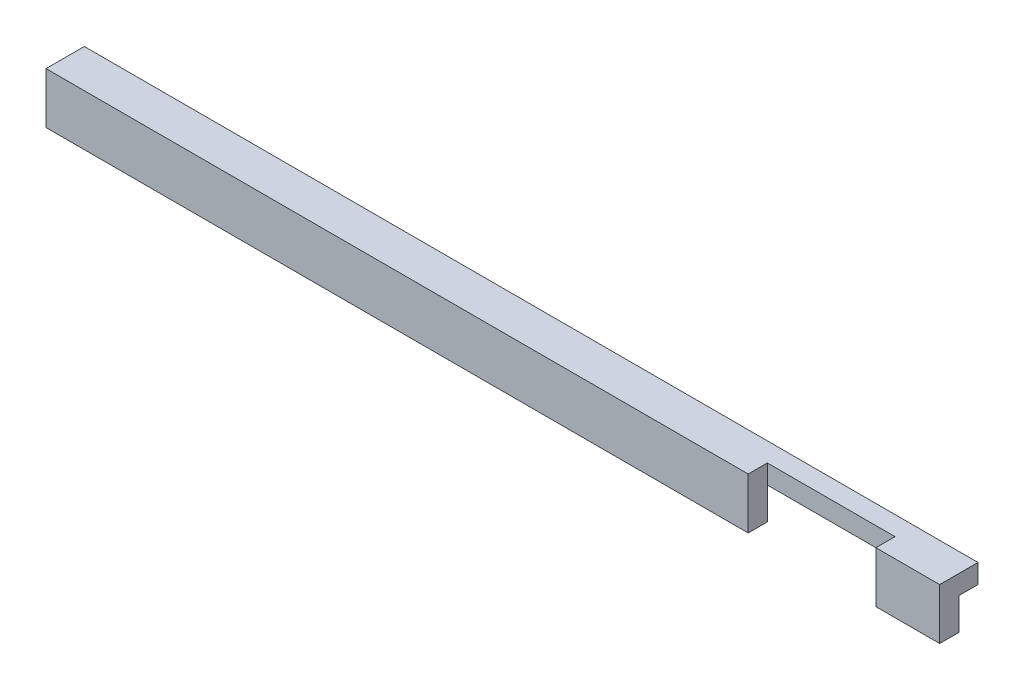
SolidWorks part; units mm, degrees
ref_plane "Front Plane" through (0, 0, 0) normal (0, 0, 1) x (1, 0, 0)
ref_plane "Top Plane" through (0, 0, 0) normal (0, 1, 0) x (1, 0, 0)
ref_plane "Right Plane" through (0, 0, 0) normal (1, 0, 0) x (0, 0, -1)
sketch "Sketch1" plane through (0, 0, 0) normal (0, 1, 0) x (1, 0, 0)
  line L1 (70, -4) -> (-70, -4)
  line L2 (70, -4) -> (70, 4)
  line L3 (70, 4) -> (-70, 4)
  line L4 (-70, -4) -> (-70, 4)
  line L5 (70, -4) -> (-70, 4) construction
  line L6 (70, 4) -> (-70, -4) construction
  point P0 (0, 0)
  dimension "D1" = 140
  dimension "D2" = 8
extrude "Boss-Extrude1" add sketch "Sketch1" along normal blind 8
ref_plane "Plane1" through (70, 0, 0) normal (1, 0, 0) x (0, 0, -1)
sketch "Sketch2" plane through (70, 0, 0) normal (1, 0, 0) x (0, 0, -1)
  line L0 (-4, 8) -> (4, 8) construction
  line L1 (4, 0) -> (1, 0)
  line L2 (4, 0) -> (4, 5)
  line L3 (4, 5) -> (1, 5)
  line L4 (1, 0) -> (1, 5)
  line L5 (-4, 0) -> (-2, 0)
  line L6 (-4, 0) -> (-4, 8)
  line L7 (-4, 8) -> (-2, 8)
  line L8 (-2, 0) -> (-2, 8)
  dimension "D1" = 3
  dimension "D2" = 5
  dimension "D3" = 2
extrude "Cut-Extrude1" cut sketch "Sketch2" against normal blind 140
ref_plane "Plane2" through (0, 0, 2) normal (0, 0, 1) x (1, 0, 0)
sketch "Sketch4" plane through (0, 0, 2) normal (0, 0, 1) x (1, 0, 0)
  line L0 (70, 4) -> (60, 4) construction
  line L1 (70, 0) -> (70, 8) construction
  line L2 (60, 4) -> (60, 8) construction
  line L3 (-70, 8) -> (70, 8) construction
  line L4 (-70, 0) -> (70, 0) construction
  line L5 (60, 8) -> (40, 8)
  line L6 (60, 8) -> (60, 0)
  line L7 (60, 0) -> (40, 0)
  line L8 (40, 8) -> (40, 0)
  dimension "D1" = 10
  dimension "D2" = 20
extrude "Cut-Extrude2" cut sketch "Sketch4" against normal blind 3
